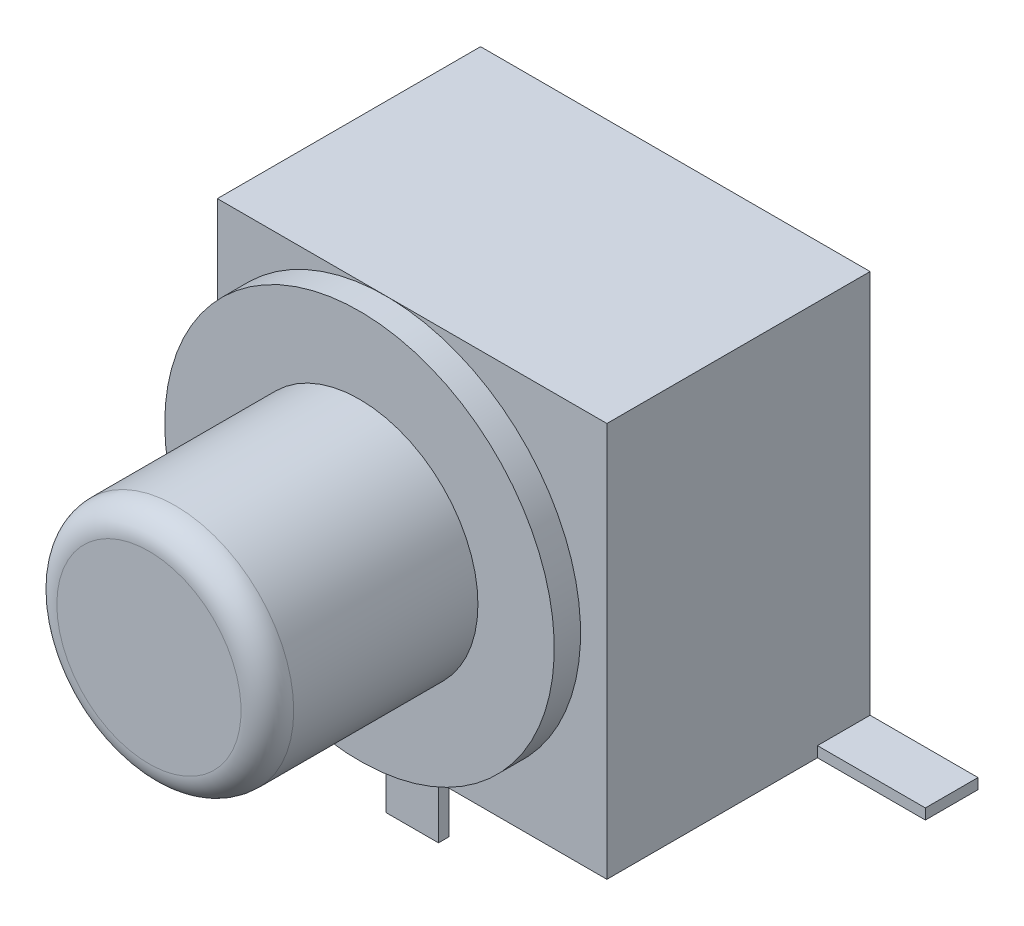
SolidWorks part; units mm, degrees
ref_plane "前视基准面" through (0, 0, 0) normal (0, 0, 1) x (1, 0, 0)
ref_plane "上视基准面" through (0, 0, 0) normal (0, 1, 0) x (1, 0, 0)
ref_plane "右视基准面" through (0, 0, 0) normal (1, 0, 0) x (0, 0, -1)
sketch "草图1" plane through (0, 0, 0) normal (0, 0, 1) x (1, 0, 0)
  line L0 (-9.0219, 0) -> (10.7811, 0) construction
  line L1 (0, 7.4002) -> (0, -7.1592) construction
  line L3 (-3.7, 3.75) -> (3.7, 3.75)
  line L4 (-3.7, 3.75) -> (-3.7, -3.75)
  line L5 (-3.7, -3.75) -> (3.7, -3.75)
  line L6 (3.7, 3.75) -> (3.7, -3.75)
  dimension "D1" = 7.4
  dimension "D2" = 7.5
extrude "凸台-拉伸1" add sketch "草图1" along normal blind 5
sketch "草图2" plane through (0, 0, 5) normal (0, 0, 1) x (1, 0, 0)
  line L0 (-3.7, 0.55) -> (3.7, 0.55) construction
  line L1 (3.7, 3.75) -> (-3.7, 3.75) construction
  line L2 (0, 4.284) -> (0, -4.4472) construction
  line L3 (3.7, -3.75) -> (3.7, 3.75) construction
  line L4 (-3.7, 3.75) -> (-3.7, -3.75) construction
  circle A0 centre (0, 0.55) radius 1.75
  dimension "D2" = 3.5
  dimension "D1" = 3.2
extrude "凸台-拉伸2" add sketch "草图2" along normal blind 2.2
ref_plane "基准面2" through (0, 0.55, 0) normal (0, 1, 0) x (1, 0, 0)
sketch "草图4" plane through (0, 0.55, 0) normal (0, 1, 0) x (1, 0, 0)
  line L0 (0, -5.5) -> (3.7, -5.5)
  line L1 (3.7, -5.5) -> (3.7, -6)
  line L2 (3.7, -6) -> (2.25, -6)
  line L3 (2.25, -6) -> (2.25, -10)
  line L4 (2.25, -10) -> (0, -10)
  line L5 (0, -10) -> (0, -5.5)
  line L6 (3.7, -5) -> (-3.7, -5) construction
  line L9 (0, 1.8312) -> (0, -11.866) construction
  dimension "D1" = 0.5
  dimension "D2" = 4.5
  dimension "D3" = 0.5
  dimension "D4" = 2.25
  dimension "D5" = 3.7
revolve "旋转1" add sketch "草图4" angle 360 about L9
fillet "圆角1" radius 0.5 1 edges at (-2.25, 0.55, 10)
sketch "草图5" plane through (3.7, 0, 0) normal (1, 0, 0) x (0, 0, -1)
  line L1 (0, -3.75) -> (-1, -3.75)
  line L2 (0, -3.75) -> (0, -3.55)
  line L3 (0, -3.55) -> (-1, -3.55)
  line L4 (-1, -3.75) -> (-1, -3.55)
  dimension "D1" = 1
  dimension "D2" = 0.2
extrude "凸台-拉伸3" add sketch "草图5" along normal blind 2.05
sketch "草图6" plane through (-3.7, 0, 0) normal (-1, 0, 0) x (0, 0, 1)
  line L1 (0, -3.75) -> (1, -3.75)
  line L2 (0, -3.75) -> (0, -3.55)
  line L3 (0, -3.55) -> (1, -3.55)
  line L4 (1, -3.75) -> (1, -3.55)
  dimension "D1" = 1
  dimension "D2" = 0.2
extrude "凸台-拉伸4" add sketch "草图6" along normal blind 2.05
sketch "草图7" plane through (0, 0, 0) normal (0, 0, -1) x (-1, 0, 0)
  line L0 (0, 4.687) -> (0, -6.5567) construction
  line L1 (-2.25, -2.0068) -> (-2.25, -6.6331) construction
  line L2 (2.25, -2.0068) -> (2.25, -6.6331) construction
  line L3 (5.75, -3.75) -> (-5.75, -3.75) construction
  line L4 (-1.9, -3.55) -> (-2.6, -3.55)
  line L5 (-1.9, -3.55) -> (-1.9, -3.75)
  line L6 (-1.9, -3.75) -> (-2.6, -3.75)
  line L7 (-2.6, -3.55) -> (-2.6, -3.75)
  line L8 (1.9, -3.55) -> (2.6, -3.55)
  line L9 (1.9, -3.55) -> (1.9, -3.75)
  line L10 (1.9, -3.75) -> (2.6, -3.75)
  line L11 (2.6, -3.55) -> (2.6, -3.75)
  dimension "D1" = 4.5
  dimension "D2" = 0.7
  dimension "D3" = 0.2
extrude "凸台-拉伸5" add sketch "草图7" along normal blind 1
sketch "草图8" plane through (0, -3.75, 0) normal (0, -1, 0) x (1, 0, 0)
  line L0 (0, -1.0352) -> (0, 10.3771) construction
  line L1 (-3.7, 5) -> (3.7, 5) construction
  line L2 (-0.5, 5) -> (0.5, 5)
  line L3 (-0.5, 5) -> (-0.5, 4.8)
  line L4 (-0.5, 4.8) -> (0.5, 4.8)
  line L5 (0.5, 5) -> (0.5, 4.8)
  dimension "D1" = 1
  dimension "D2" = 0.2
extrude "凸台-拉伸6" add sketch "草图8" along normal blind 1
